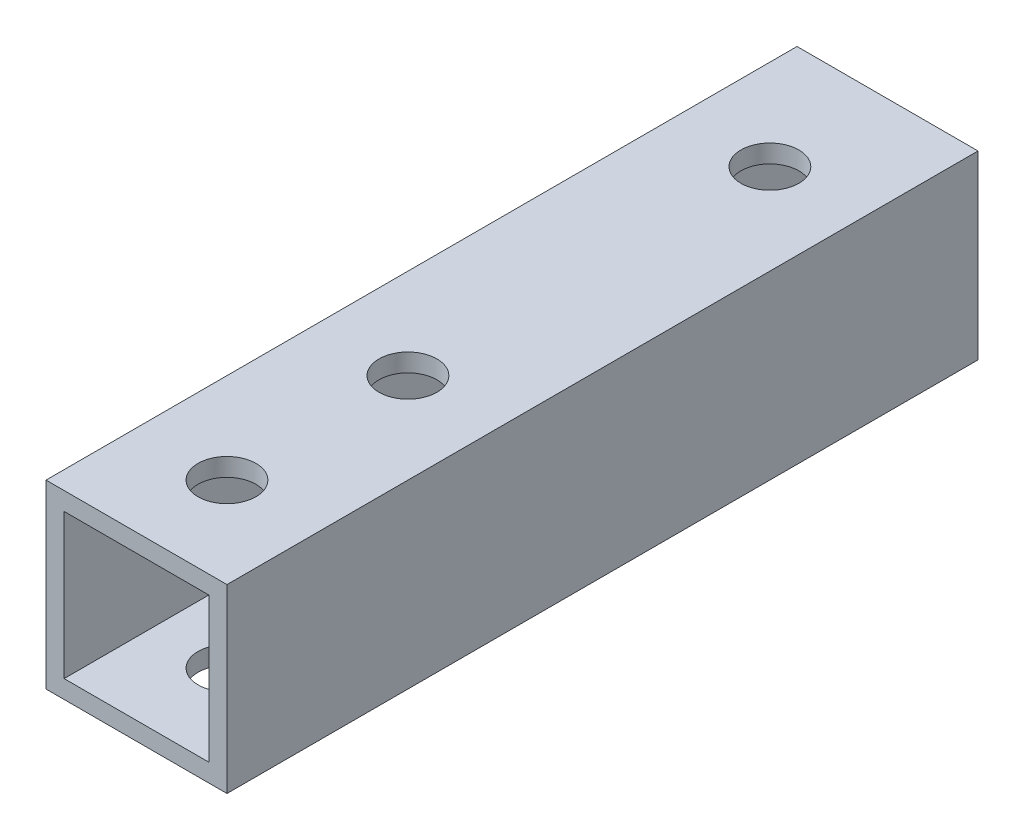
SolidWorks part; units mm, degrees
material "1060 合金"
ref_plane "正面" through (0, 0, 0) normal (0, 0, 1) x (1, 0, 0)
ref_plane "平面" through (0, 0, 0) normal (0, 1, 0) x (1, 0, 0)
ref_plane "右側面" through (0, 0, 0) normal (1, 0, 0) x (0, 0, -1)
sketch "ｽｹｯﾁ1" plane through (0, 0, 0) normal (0, 0, 1) x (1, 0, 0)
  line L1 (-5, -5) -> (5, -5)
  line L2 (-5, -5) -> (-5, 5)
  line L3 (-5, 5) -> (5, 5)
  line L4 (5, -5) -> (5, 5)
  line L5 (-5, -5) -> (5, 5) construction
  line L6 (-5, 5) -> (5, -5) construction
  point P0 (0, 0)
  dimension "D1" = 10
extrude "押し出し-薄板1" add sketch "ｽｹｯﾁ1" along normal blind 41.5 thin thin type one direction reverse wall 1
sketch "ｽｹｯﾁ2" plane through (0, 5, 0) normal (0, 1, 0) x (1, 0, 0)
  line L0 (0, 0) -> (0, -41.5) construction
  line L1 (5, -41.5) -> (-5, -41.5) construction
  circle A0 centre (0, -6.5) radius 1.6
  circle A1 centre (0, -26.5) radius 1.6
  circle A2 centre (0, -36.5) radius 1.6
  dimension "D1" = 6.5
  dimension "D2" = 20
  dimension "D3" = 3.2
  dimension "D4" = 5
extrude "ｶｯﾄ - 押し出し1" cut sketch "ｽｹｯﾁ2" against normal blind 10 contours L0 A0 | L0 A0 | L0 A1 | L0 A1 | A2
